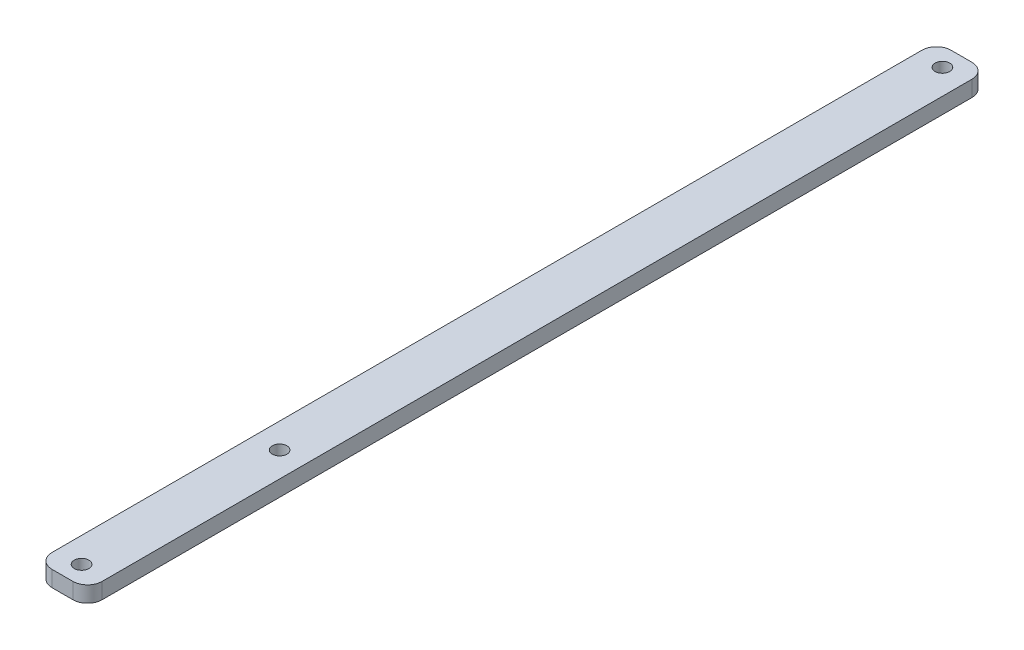
SolidWorks part; units mm, degrees
ref_plane "Front Plane" through (0, 0, 0) normal (0, 0, 1) x (1, 0, 0)
ref_plane "Top Plane" through (0, 0, 0) normal (0, 1, 0) x (1, 0, 0)
ref_plane "Right Plane" through (0, 0, 0) normal (1, 0, 0) x (0, 0, -1)
sketch "Sketch1" plane through (0, 0, 0) normal (0, 1, 0) x (1, 0, 0)
  line L0 (0, 85.845) -> (0, 0) construction
  line L1 (-5, 89.655) -> (5, 89.655)
  line L2 (-5, 89.655) -> (-5, -89.655)
  line L3 (-5, -89.655) -> (5, -89.655)
  line L4 (5, 89.655) -> (5, -89.655)
  line L5 (-5, 89.655) -> (5, -89.655) construction
  line L6 (-5, -89.655) -> (5, 89.655) construction
  line L7 (0, 0) -> (0, -85.845) construction
  circle A0 centre (0, 85.845) radius 1.4605
  circle A1 centre (0, -46.345) radius 1.4605
  circle A2 centre (0, -85.845) radius 1.4605
  point P0 (0, 0)
  point P12 (0, 0)
  dimension "D3" = 2.921
  dimension "D1" = 179.31
  dimension "D2" = 10
  dimension "D4" = 39.5
  dimension "D5" = 171.69
extrude "Boss-Extrude1" add sketch "Sketch1" along normal blind 3.175
fillet "Fillet1" radius 2.921 4 edges at (5, 1.5875, -89.655) (-5, 1.5875, -89.655) (-5, 1.5875, 89.655) (5, 1.5875, 89.655)
